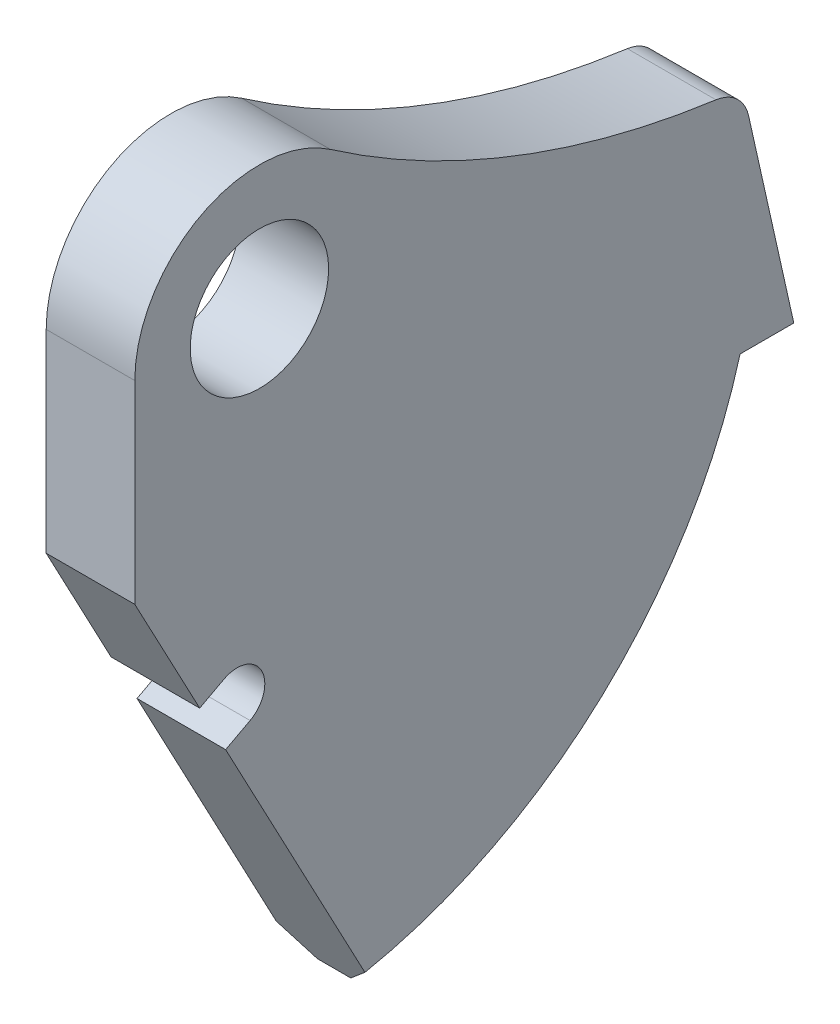
SolidWorks part; units mm, degrees
material "Q355"
ref_plane "前视基准面" through (0, 0, 0) normal (0, 0, 1) x (1, 0, 0)
ref_plane "上视基准面" through (0, 0, 0) normal (0, 1, 0) x (1, 0, 0)
ref_plane "右视基准面" through (0, 0, 0) normal (1, 0, 0) x (0, 0, -1)
sketch "草图1" plane through (0, 0, 0) normal (1, 0, 0) x (0, 0, -1)
  line L0 (-22.5, 0) -> (-22.5, -35)
  line L1 (-22.5, -35) -> (-10.7832, -57.0843)
  line L2 (96.5, -50.5) -> (88.3313, -13.9723)
  line L3 (96.5, -50.5) -> (91.9819, -50.5)
  line L4 (-10.7832, -57.0843) -> (-6.3663, -54.7409)
  line L5 (-6.0964, -65.918) -> (-1.6796, -63.5746)
  line L6 (-6.0964, -65.918) -> (21.5, -117.9327)
  circle A0 centre (0, 0) radius 12.5
  arc A1 (12.8197, 18.4907) -> (-22.5, 0) centre (0, 0) ccw
  arc A2 (88.3313, -13.9723) -> (82.4424, -8.5637) centre (81.5, -15.5) ccw
  arc A3 (12.8197, 18.4907) -> (82.4424, -8.5637) centre (103.9823, 149.9797) ccw
  arc A4 (21.5, -117.9327) -> (91.9819, -50.5) centre (2, -27) ccw
  arc A5 (-1.6796, -63.5746) -> (-6.3663, -54.7409) centre (-4.0229, -59.1578) ccw
  dimension "D1" = 12.5
  dimension "D2" = 22.5
  dimension "D3" = 7
  dimension "D5" = 160
  dimension "D10" = 93
  dimension "D14" = 5
  dimension "D4" = 81.5
  dimension "D6" = 35
  dimension "D7" = 96.5
  dimension "D8" = 15.5
  dimension "D9" = 50.5
  dimension "D11" = 27
  dimension "D12" = 2
  dimension "D13" = 44
  dimension "D15" = 25
extrude "凸台-拉伸1" add sketch "草图1" along normal mid plane 16
chamfer "倒角1" distance 5 angle 45 2 edges at (-8, -94.1985, -66.2913) (8, -94.1985, -66.2913)
